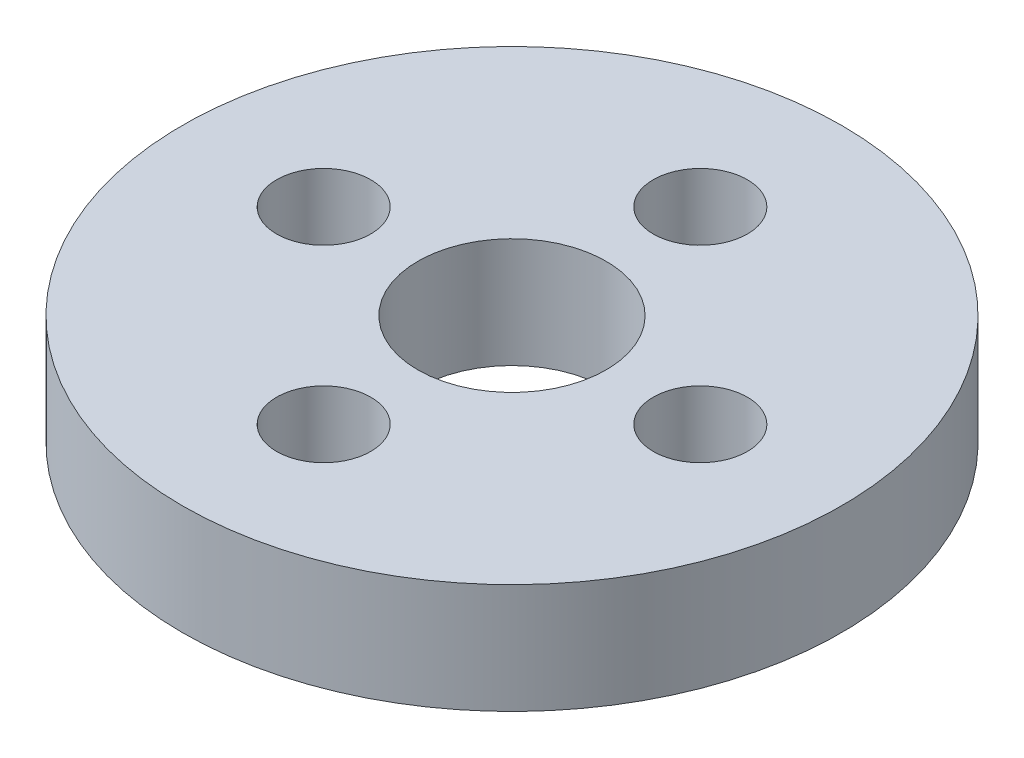
SolidWorks part; units mm, degrees
material "PE High Density"
ref_plane "Front Plane" through (0, 0, 0) normal (0, 0, 1) x (1, 0, 0)
ref_plane "Top Plane" through (0, 0, 0) normal (0, 1, 0) x (1, 0, 0)
ref_plane "Right Plane" through (0, 0, 0) normal (1, 0, 0) x (0, 0, -1)
sketch "Sketch1" plane through (0, 0, 0) normal (0, 1, 0) x (1, 0, 0)
  circle A0 centre (0, 0) radius 10.5
  dimension "D1" = 21
extrude "Boss-Extrude1" add sketch "Sketch1" along normal blind 3.5
sketch "Sketch2" plane through (0, 3.5, 0) normal (0, 1, 0) x (1, 0, 0)
  line L0 (0, 0) -> (0, 6) construction
  circle A0 centre (0, 0) radius 3
  circle A1 centre (0, 6) radius 1.5
  circle A2 centre (6, 0) radius 1.5
  circle A3 centre (0, -6) radius 1.5
  circle A4 centre (-6, 0) radius 1.5
  point P14 (0, 0)
  dimension "D1" = 4
  dimension "D2" = 6
  dimension "D3" = 6
extrude "Cut-Extrude1" cut sketch "Sketch2" against normal blind 10.2
